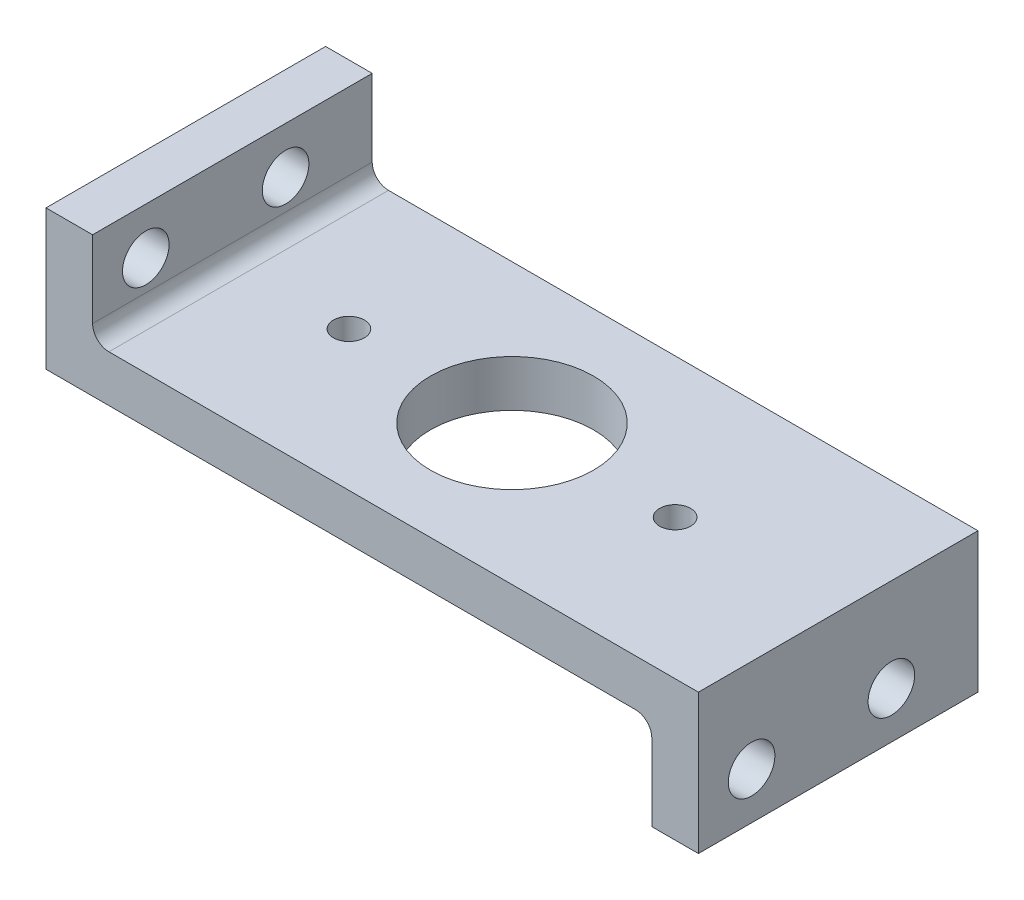
SolidWorks part; units mm, degrees
material "Alloy Steel"
ref_plane "Front Plane" through (0, 0, 0) normal (0, 0, 1) x (1, 0, 0)
ref_plane "Top Plane" through (0, 0, 0) normal (0, 1, 0) x (1, 0, 0)
ref_plane "Right Plane" through (0, 0, 0) normal (1, 0, 0) x (0, 0, -1)
sketch "Sketch1" plane through (0, 0, 0) normal (0, 0, 1) x (1, 0, 0)
  line L0 (-88.9, 31.75) -> (-88.9, -6.35)
  line L1 (-88.9, -6.35) -> (71.755, -6.35)
  line L2 (76.2, -10.795) -> (76.2, -31.75)
  line L3 (76.2, -31.75) -> (88.9, -31.75)
  line L4 (88.9, -31.75) -> (88.9, 6.35)
  line L5 (88.9, 6.35) -> (-71.755, 6.35)
  line L6 (-76.2, 10.795) -> (-76.2, 31.75)
  line L7 (-76.2, 31.75) -> (-88.9, 31.75)
  arc A0 (71.755, -6.35) -> (76.2, -10.795) centre (71.755, -10.795) cw
  arc A1 (-71.755, 6.35) -> (-76.2, 10.795) centre (-71.755, 10.795) cw
  dimension "D8" = 4.445
  dimension "D1" = 6.35
  dimension "D2" = 12.7
  dimension "D3" = 38.1
  dimension "D4" = 63.5
  dimension "D5" = 88.9
  dimension "D6" = 177.8
  dimension "D7" = 6.35
extrude "Boss-Extrude1" add sketch "Sketch1" along normal mid plane 76.2
hole_wizard "1/2 (0.5) Diameter Hole1" positions "Sketch2" profile "Sketch3" hole size "1/2" standard "ANSI Inch" end condition through all
sketch "Sketch2" plane through (88.9, 0, 0) normal (1, 0, 0) x (0, 0, -1)
  line L0 (-38.1, 31.75) -> (38.1, 31.75) construction
  line L1 (-38.1, -31.75) -> (38.1, -31.75) construction
  point P0 (-23.6065, -19.05)
  point P2 (14.4935, -19.05)
  point P4 (-23.6065, 19.05)
  point P6 (14.4935, 19.05)
  dimension "D1" = 38.1
  dimension "D2" = 12.7
  dimension "D3" = 12.7
sketch "Sketch3" plane through (88.9, -19.05, 23.6065) normal (0, 1, 0) x (0, 0, -1)
  line L0 (0, 0) -> (0, 177.8)
  line L1 (0, 177.8) -> (6.35, 177.8)
  line L2 (6.35, 177.8) -> (6.35, 0)
  line L5 (6.35, 0) -> (0, 0)
  line L11 (0, -6.35) -> (0, 107.95) construction
  dimension "Thru Hole Dia." = 12.7
  dimension "Thru Hole Depth" = 177.8
sketch "Sketch4" plane through (0, 6.35, 0) normal (0, 1, 0) x (1, 0, 0)
  circle A0 centre (0, 0) radius 22.225
  dimension "D1" = 44.45
extrude "Cut-Extrude1" cut sketch "Sketch4" against normal through all
hole_wizard "3/8-24 Tapped Hole1" positions "Sketch7" profile "Sketch8" tap size "3/8-24" standard "ANSI Inch" end condition through all
sketch "Sketch7" plane through (0, 6.35, 0) normal (0, 1, 0) x (1, 0, 0)
  circle A0 centre (0, 0) radius 22.225 construction
  point P0 (44.45, 0)
  point P2 (-44.45, 0)
  dimension "D1" = 44.45
  dimension "D2" = 44.45
sketch "Sketch8" plane through (44.45, 6.35, 0) normal (1, 0, 0) x (0, 0, 1)
  line L0 (0, 0) -> (0, 38.1)
  line L1 (0, 38.1) -> (4.2164, 38.1)
  line L2 (4.2164, 38.1) -> (4.2164, 0)
  line L5 (4.2164, 0) -> (0, 0)
  line L11 (0, -6.35) -> (0, 107.95) construction
  dimension "Thru Tap Drill Dia." = 8.4328
  dimension "Thru Tap Drill Depth" = 38.1
cosmetic thread "Hole Thread1" parameters "D2"=9.525
cosmetic thread "Hole Thread2" parameters "D2"=9.525
